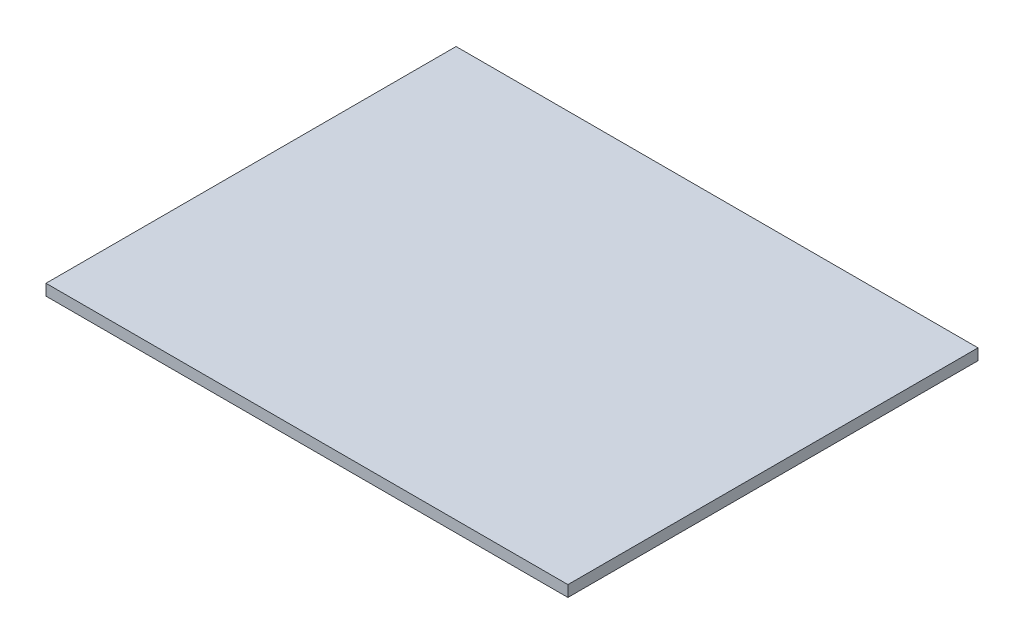
SolidWorks part; units mm, degrees
material "Glass"
ref_plane "Front Plane" through (0, 0, 0) normal (0, 0, 1) x (1, 0, 0)
ref_plane "Top Plane" through (0, 0, 0) normal (0, 1, 0) x (1, 0, 0)
ref_plane "Right Plane" through (0, 0, 0) normal (1, 0, 0) x (0, 0, -1)
sketch "Sketch1" plane through (0, 0, 0) normal (0, 1, 0) x (1, 0, 0)
  line L0 (0, 37.0077) -> (0, -43.1852) construction
  line L1 (57.5422, 0) -> (-54.911, 0) construction
  line L3 (35, 27.5) -> (-35, 27.5)
  line L4 (35, 27.5) -> (35, -27.5)
  line L5 (35, -27.5) -> (-35, -27.5)
  line L6 (-35, 27.5) -> (-35, -27.5)
  line L7 (35, 27.5) -> (-35, -27.5) construction
  line L8 (35, -27.5) -> (-35, 27.5) construction
  point P5 (0, 0)
  dimension "D1" = 70
  dimension "D2" = 55
extrude "Boss-Extrude1" add sketch "Sketch1" along normal blind 1.5
